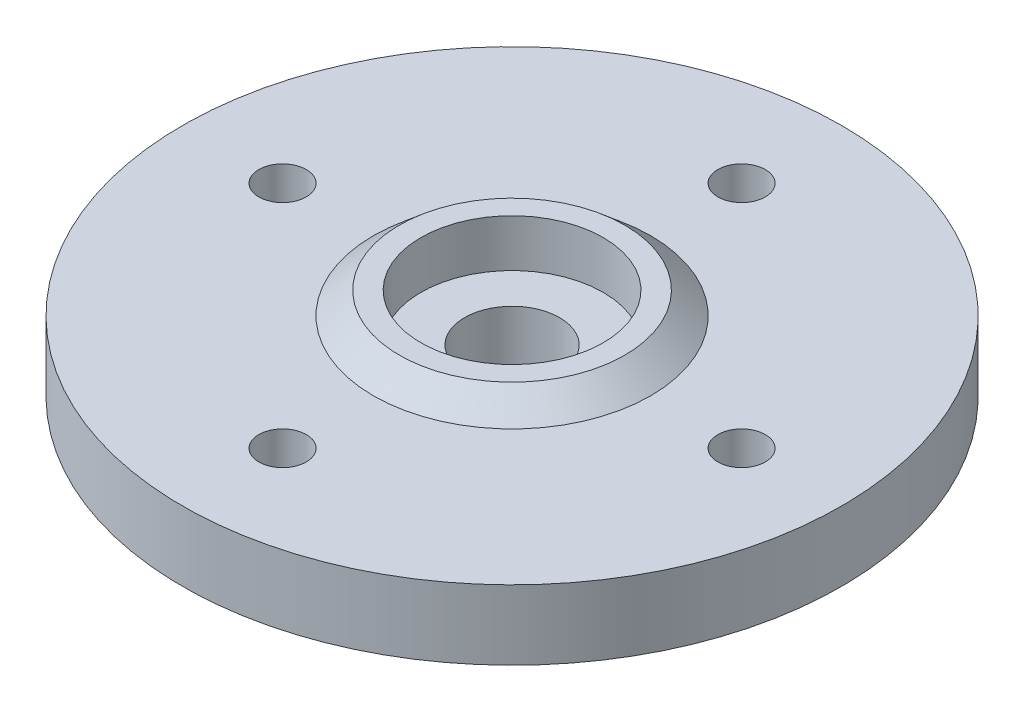
SolidWorks part; units mm, degrees
ref_plane "前视基准面" through (0, 0, 0) normal (0, 0, 1) x (1, 0, 0)
ref_plane "上视基准面" through (0, 0, 0) normal (0, 1, 0) x (1, 0, 0)
ref_plane "右视基准面" through (0, 0, 0) normal (1, 0, 0) x (0, 0, -1)
other "Configuration Table"
sketch "草图1" plane through (0, 0, 0) normal (0, 0, 1) x (1, 0, 0)
  line L0 (-2.88, 0) -> (-2.88, 2.9)
  line L1 (-2.88, 2.9) -> (-1.5, 2.9)
  line L2 (-1.5, 2.9) -> (-1.5, 4.6)
  line L3 (-1.5, 4.6) -> (-2.88, 4.6)
  line L4 (-2.88, 4.6) -> (-2.88, 6.1)
  line L5 (-2.88, 6.1) -> (-3.56, 6.1)
  line L6 (-3.56, 6.1) -> (-4.38, 5.4)
  line L7 (-4.38, 5.4) -> (-10.41, 5.4)
  line L8 (-10.41, 5.4) -> (-10.41, 3.2)
  line L9 (-10.41, 3.2) -> (-4.33, 3.2)
  line L10 (-4.33, 3.2) -> (-4.33, 0)
  line L11 (-4.33, 0) -> (-2.88, 0)
  line L12 (0, 0) -> (0, 0.9681) construction
  dimension "D1" = 1.45
  dimension "D2" = 3
  dimension "D3" = 5.76
  dimension "D4" = 2.9
  dimension "D5" = 1.7
  dimension "D6" = 1.5
  dimension "D7" = 0.68
  dimension "D8" = 2.2
  dimension "D9" = 6.03
  dimension "D10" = 6.08
  dimension "D11" = 3.2
revolve "旋转1" add sketch "草图1" angle 360 about L12
sketch "草图2" plane through (0, 5.4, 0) normal (0, 1, 0) x (1, 0, 0)
  line L0 (0, 0) -> (0, 7.25) construction
  circle A0 centre (0, 7.25) radius 0.75
  circle A1 centre (7.25, 0) radius 0.75
  circle A2 centre (0, -7.25) radius 0.75
  circle A3 centre (-7.25, 0) radius 0.75
  point P12 (0, 0)
  dimension "D2" = 1.5
  dimension "D1" = 7.25
  dimension "D3" = 4
extrude "转盘孔-切除-拉伸" cut sketch "草图2" against normal through all
